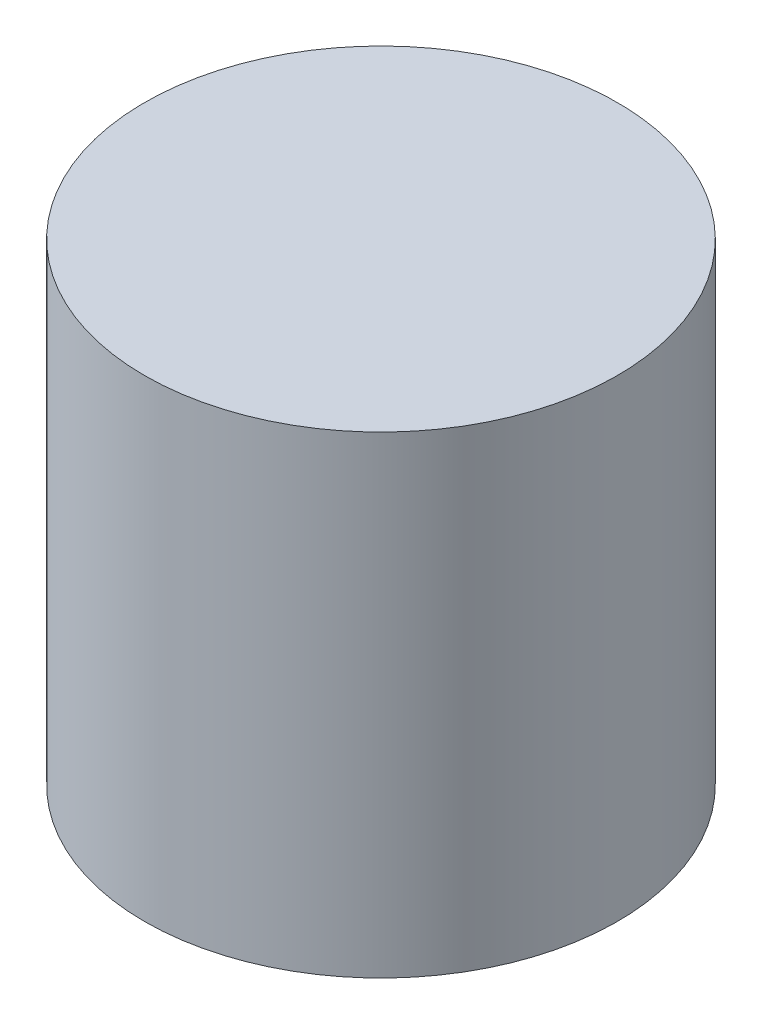
SolidWorks part; units mm, degrees
material "EPDM 60 硬度计"
ref_plane "前视基准面" through (0, 0, 0) normal (0, 0, 1) x (1, 0, 0)
ref_plane "上视基准面" through (0, 0, 0) normal (0, 1, 0) x (1, 0, 0)
ref_plane "右视基准面" through (0, 0, 0) normal (1, 0, 0) x (0, 0, -1)
sketch "草图1" plane through (0, 0, 0) normal (0, 1, 0) x (1, 0, 0)
  circle A0 centre (0, 0) radius 92.5
extrude "凸台-拉伸1" add sketch "草图1" along normal blind 185 contours A0
sketch "草图2" plane through (0, 0, 0) normal (0, -1, 0) x (-1, 0, 0)
  circle A0 centre (0, 0) radius 50
extrude "切除-拉伸1" cut sketch "草图2" against normal blind 50
